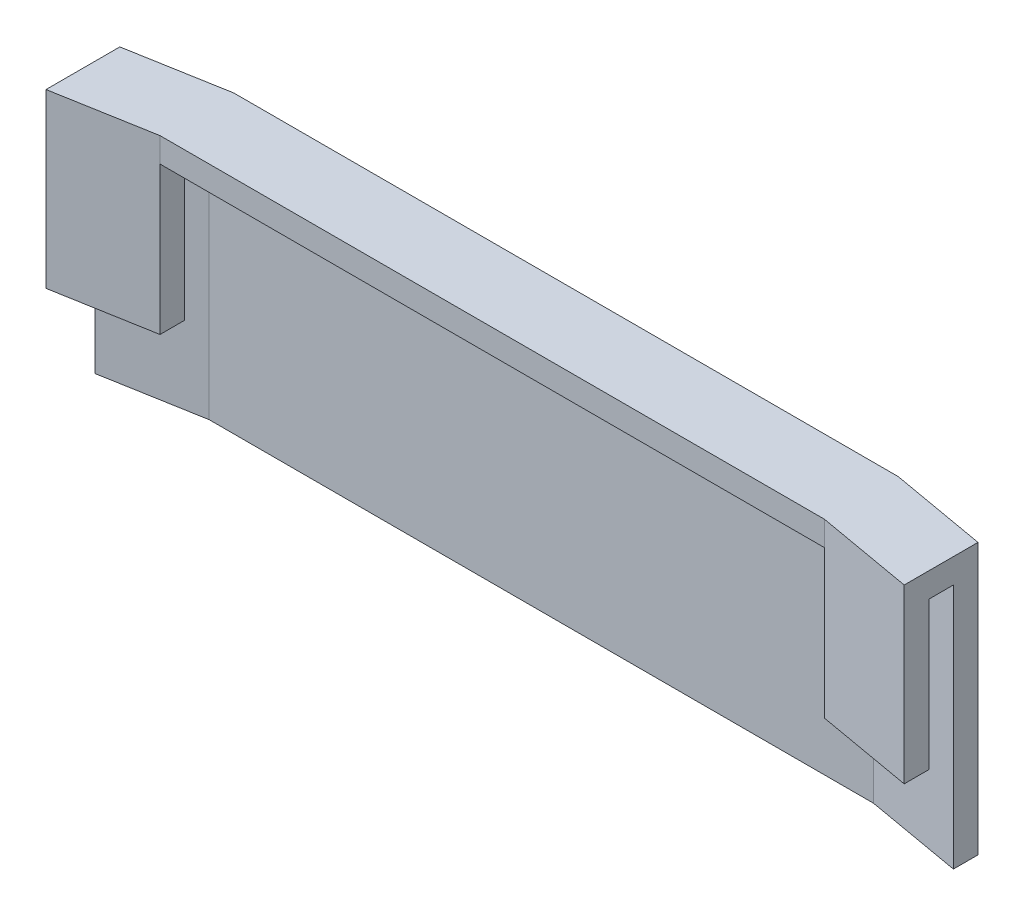
SolidWorks part; units mm, degrees
ref_plane "Front Plane" through (0, 0, 0) normal (0, 0, 1) x (1, 0, 0)
ref_plane "Top Plane" through (0, 0, 0) normal (0, 1, 0) x (1, 0, 0)
ref_plane "Right Plane" through (0, 0, 0) normal (1, 0, 0) x (0, 0, -1)
sketch "Sketch1" plane through (0, 0, 0) normal (0, 1, 0) x (1, 0, 0)
  line L4 (-27, 0) -> (27, 0)
  line L5 (27, 0) -> (34.8785, -1.3892)
  line L6 (-27, 0) -> (-34.8785, -1.3892)
  line L7 (-34.8785, -1.3892) -> (34.8785, -1.3892) construction
  line L8 (34.8785, -1.3892) -> (34.8785, 4.6108)
  line L9 (-34.8785, -1.3892) -> (-34.8785, 4.6108)
  line L10 (-34.8785, 4.6108) -> (-27, 6)
  line L11 (-27, 6) -> (27, 6)
  line L12 (27, 6) -> (34.8785, 4.6108)
  dimension "D1" = 54
  dimension "D2" = 27
  dimension "D3" = 10
  dimension "D4" = 10
  dimension "D5" = 8
  dimension "D6" = 6
  dimension "D7" = 54
  dimension "D8" = 6
extrude "Boss-Extrude1" add sketch "Sketch1" along normal blind 2
sketch "Sketch3" plane through (0, 2, 0) normal (0, 1, 0) x (1, 0, 0)
  line L0 (-27, 4) -> (27, 4)
  line L4 (34.8785, 4.6108) -> (27, 6)
  line L5 (27, 6) -> (-27, 6)
  line L6 (-27, 6) -> (-34.8785, 4.6108)
  line L10 (34.8785, 4.6108) -> (34.8785, 2.6108)
  line L11 (34.8785, -1.3892) -> (34.8785, 4.6108) construction
  line L12 (-34.8785, 4.6108) -> (-34.8785, 2.6108)
  line L13 (-34.8785, 4.6108) -> (-34.8785, -1.3892) construction
  line L14 (-27, 4) -> (-34.8785, 2.6108)
  line L15 (27, 4) -> (34.8785, 2.6108)
  dimension "D1" = 2
  dimension "D2" = 2
  dimension "D3" = 2
  dimension "D4" = 54
  dimension "D5" = 8
extrude "Boss-Extrude5" add sketch "Sketch3" against normal blind 22
sketch "Sketch8" plane through (0, 0, 0) normal (0, -1, 0) x (1, 0, 0)
  line L0 (-34.8785, 1.3892) -> (-34.8785, -0.6108)
  line L1 (-34.8785, -2.6108) -> (-34.8785, 1.3892) construction
  line L2 (-34.8785, 1.3892) -> (-27, 0)
  line L4 (27, 0) -> (34.8785, 1.3892)
  line L5 (34.8785, 1.3892) -> (34.8785, -0.6108)
  line L6 (34.8785, 1.3892) -> (34.8785, -2.6108) construction
  line L7 (34.8785, -0.6108) -> (27, -2)
  line L9 (-27, -2) -> (-34.8785, -0.6108)
  line L10 (-27, 0) -> (-27, -2)
  line L11 (27, 0) -> (27, -2)
extrude "Boss-Extrude6" add sketch "Sketch8" along normal blind 12
